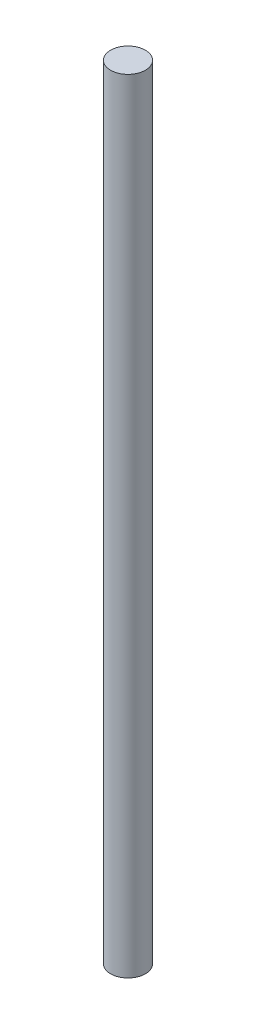
SolidWorks part; units mm, degrees
ref_plane "Спереди" through (0, 0, 0) normal (0, 0, 1) x (1, 0, 0)
ref_plane "Сверху" through (0, 0, 0) normal (0, 1, 0) x (1, 0, 0)
ref_plane "Справа" through (0, 0, 0) normal (1, 0, 0) x (0, 0, -1)
sketch "Эскиз1" plane through (0, 0, 0) normal (0, 1, 0) x (1, 0, 0)
  circle A0 centre (0, 0) radius 0.1
  dimension "D1" = 0.2
extrude "Бобышка-Вытянуть1" add sketch "Эскиз1" along normal blind 4.5
